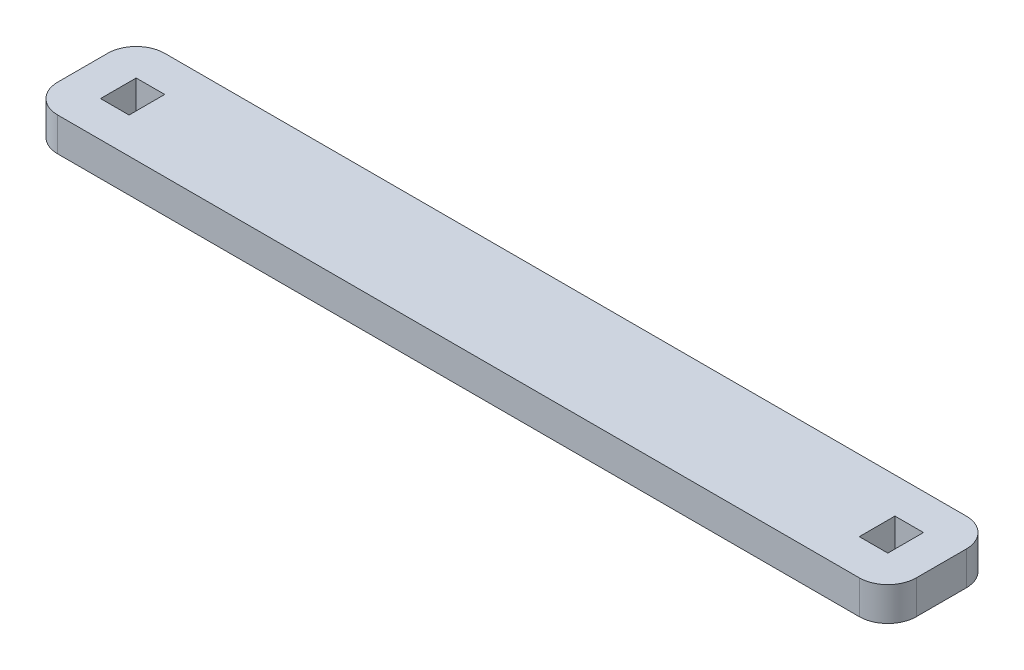
SolidWorks part; units mm, degrees
ref_plane "Front Plane" through (0, 0, 0) normal (0, 0, 1) x (1, 0, 0)
ref_plane "Top Plane" through (0, 0, 0) normal (0, 1, 0) x (1, 0, 0)
ref_plane "Right Plane" through (0, 0, 0) normal (1, 0, 0) x (0, 0, -1)
sketch "Sketch1" plane through (0, 0, 0) normal (0, 1, 0) x (1, 0, 0)
  line L0 (-33.782, 0) -> (33.782, 0) construction
  line L6 (38.227, -4.7625) -> (-38.227, -4.7625)
  line L7 (-32.512, -1.5875) -> (-35.052, -1.5875)
  line L8 (-32.512, -1.5875) -> (-32.512, 1.5875)
  line L9 (-32.512, 1.5875) -> (-35.052, 1.5875)
  line L10 (-35.052, -1.5875) -> (-35.052, 1.5875)
  line L11 (-32.512, -1.5875) -> (-35.052, 1.5875) construction
  line L12 (-32.512, 1.5875) -> (-35.052, -1.5875) construction
  line L13 (35.052, -1.5875) -> (32.512, -1.5875)
  line L14 (35.052, -1.5875) -> (35.052, 1.5875)
  line L15 (35.052, 1.5875) -> (32.512, 1.5875)
  line L16 (32.512, -1.5875) -> (32.512, 1.5875)
  line L17 (35.052, -1.5875) -> (32.512, 1.5875) construction
  line L18 (35.052, 1.5875) -> (32.512, -1.5875) construction
  line L19 (38.227, -4.7625) -> (38.227, 4.7625)
  line L20 (38.227, 4.7625) -> (-38.227, 4.7625)
  line L21 (-38.227, -4.7625) -> (-38.227, 4.7625)
  line L22 (38.227, -4.7625) -> (-38.227, 4.7625) construction
  line L23 (38.227, 4.7625) -> (-38.227, -4.7625) construction
  point P0 (0, 0)
  point P1 (0, 0)
  point P6 (-33.782, 0)
  point P11 (33.782, 0)
  dimension "D1" = 9.525
  dimension "D2" = 3.175
  dimension "D3" = 2.54
  dimension "D4" = 67.564
  dimension "D5" = 3.175
extrude "Boss-Extrude1" add sketch "Sketch1" along normal mid plane 3
fillet "Fillet1" radius 2.54 4 edges at (-38.227, 0, -4.7625) (38.227, 0, -4.7625) (38.227, 0, 4.7625) (-38.227, 0, 4.7625)
